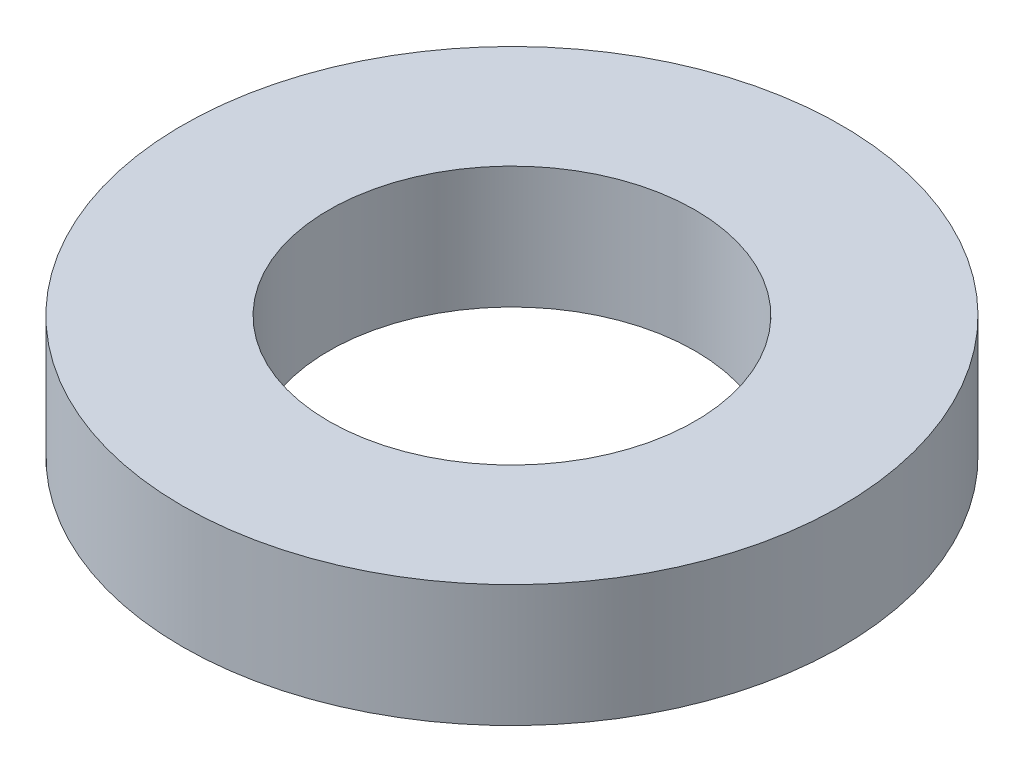
SolidWorks part; units mm, degrees
ref_plane "Front Plane" through (0, 0, 0) normal (0, 0, 1) x (1, 0, 0)
ref_plane "Top Plane" through (0, 0, 0) normal (0, 1, 0) x (1, 0, 0)
ref_plane "Right Plane" through (0, 0, 0) normal (1, 0, 0) x (0, 0, -1)
sketch "Sketch1" plane through (0, 0, 0) normal (0, 1, 0) x (1, 0, 0)
  circle A0 centre (0, 0) radius 7.5
  circle A1 centre (0, 0) radius 13.5
  dimension "D1" = 15
  dimension "D2" = 27
extrude "Boss-Extrude1" add sketch "Sketch1" along normal blind 5 contours A1 A0
